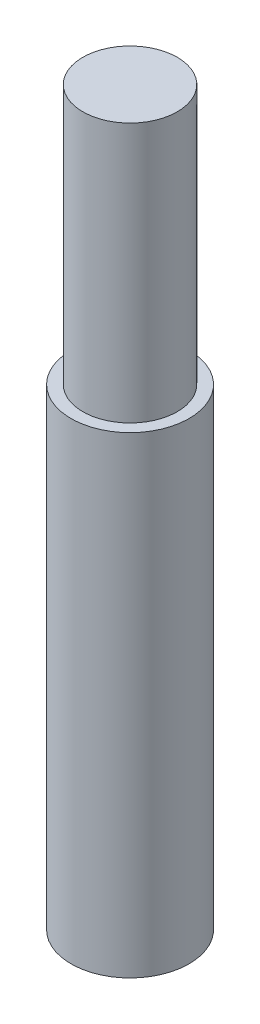
SolidWorks part; units mm, degrees
ref_plane "Ön Düzlem" through (0, 0, 0) normal (0, 0, 1) x (1, 0, 0)
ref_plane "Üst Düzlem" through (0, 0, 0) normal (0, 1, 0) x (1, 0, 0)
ref_plane "Sağ Düzlem" through (0, 0, 0) normal (1, 0, 0) x (0, 0, -1)
sketch "Çizim1" plane through (0, 0, 0) normal (0, 0, 1) x (1, 0, 0)
  line L0 (0, 0) -> (0, 31)
  line L1 (0, 31) -> (2, 31)
  line L2 (2, 31) -> (2, 20)
  line L3 (2, 20) -> (2.5, 20)
  line L4 (2.5, 20) -> (2.5, 0)
  line L5 (2.5, 0) -> (0, 0)
  line L6 (2, 24) -> (-2, 24) construction
  point P3 (2, 24)
  dimension "D1" = 7
  dimension "D2" = 2
  dimension "D3" = 2.5
  dimension "D4" = 20
revolve "Döndür1" add sketch "Çizim1" angle 360 about L0
sketch "Çizim2" plane through (0, 0, 0) normal (0, -1, 0) x (1, 0, 0)
  circle A0 centre (0, 0) radius 2
  dimension "D1" = 4
extrude "Kes-Ekstrüzyon1" cut sketch "Çizim2" against normal blind 10
fillet "Radyus1" radius 0.4 1 edges at (0, 0, -2)
